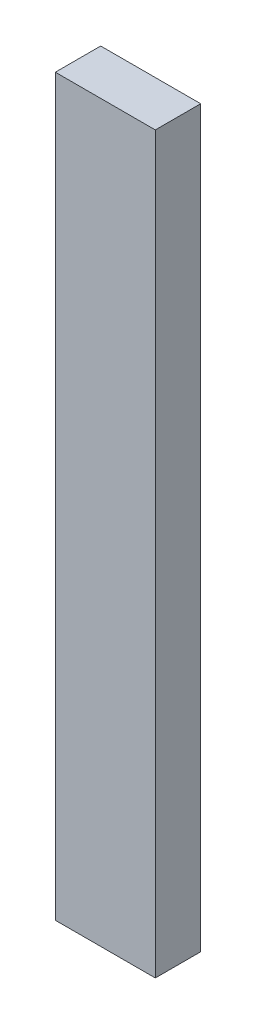
SolidWorks part; units mm, degrees
material "Pine"
ref_plane "Front Plane" through (0, 0, 0) normal (0, 0, 1) x (1, 0, 0)
ref_plane "Top Plane" through (0, 0, 0) normal (0, 1, 0) x (1, 0, 0)
ref_plane "Right Plane" through (0, 0, 0) normal (1, 0, 0) x (0, 0, -1)
sketch "Sketch1" plane through (0, 0, 0) normal (0, 1, 0) x (1, 0, 0)
  line L1 (0, 0) -> (54, 0)
  line L2 (0, 0) -> (0, 24.5)
  line L3 (0, 24.5) -> (54, 24.5)
  line L4 (54, 0) -> (54, 24.5)
  line L5 (0, 0) -> (54, 24.5) construction
  line L6 (0, 24.5) -> (54, 0) construction
  point P4 (27, 12.25)
  dimension "D1" = 24.5
  dimension "D2" = 54
extrude "Boss-Extrude1" add sketch "Sketch1" along normal blind 396.7
